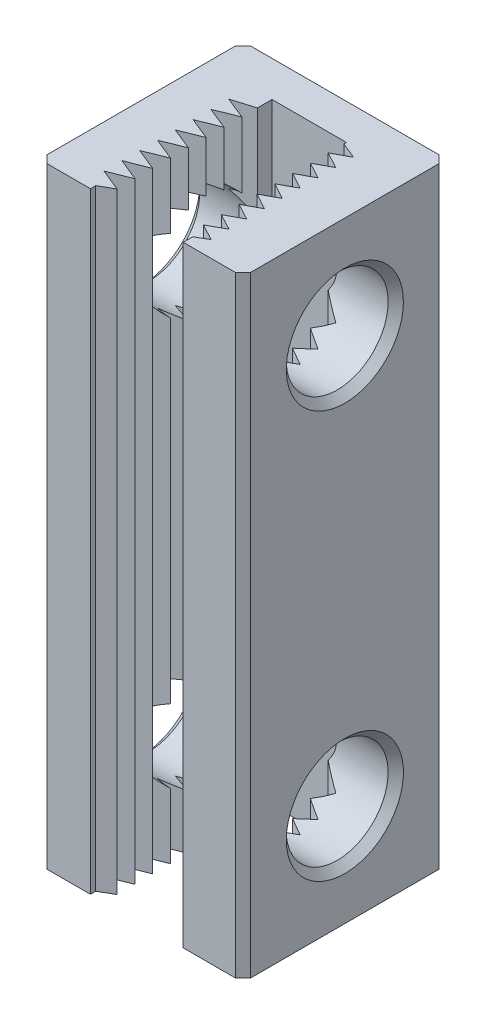
SolidWorks part; units mm, degrees
ref_plane "Front Plane" through (0, 0, 0) normal (0, 0, 1) x (1, 0, 0)
ref_plane "Top Plane" through (0, 0, 0) normal (0, 1, 0) x (1, 0, 0)
ref_plane "Right Plane" through (0, 0, 0) normal (1, 0, 0) x (0, 0, -1)
sketch "Sketch1" plane through (0, 0, 0) normal (0, 1, 0) x (1, 0, 0)
  line L1 (0, 0) -> (8, 0)
  line L2 (0, 0) -> (0, 8)
  line L3 (0, 8) -> (8, 8)
  line L4 (8, 0) -> (8, 8)
  dimension "D1" = 8
  dimension "D2" = 8
extrude "Boss-Extrude1" add sketch "Sketch1" along normal blind 300
sketch "Sketch2" plane through (0, 0, 0) normal (0, -1, 0) x (1, 0, 0)
  line L0 (5.652, 0) -> (2.0084, 0)
  line L1 (2.0084, 0) -> (2.0084, -0.2082)
  line L2 (2.0084, -0.2082) -> (2.54, -0.5151)
  line L3 (2.54, -0.5151) -> (1.6737, -0.8651)
  line L4 (1.6737, -0.8651) -> (2.54, -1.2151)
  line L5 (2.54, -1.2151) -> (1.6737, -1.5727)
  line L6 (1.6737, -1.5727) -> (2.54, -1.9151)
  line L7 (2.54, -1.9151) -> (1.6737, -2.2651)
  line L8 (1.6737, -2.2651) -> (2.54, -2.6151)
  line L9 (2.54, -2.6151) -> (1.6737, -2.9651)
  line L10 (1.6737, -2.9651) -> (2.54, -3.3151)
  line L11 (2.54, -3.3151) -> (1.6737, -3.6651)
  line L12 (1.6737, -3.6651) -> (2.54, -4.0151)
  line L13 (2.54, -4.0151) -> (1.6737, -4.3651)
  line L14 (1.6737, -4.3651) -> (2.54, -4.7151)
  line L15 (2.54, -4.7151) -> (1.6737, -5.0651)
  line L16 (1.6737, -5.0651) -> (2.54, -5.4151)
  line L17 (2.54, -5.4151) -> (1.6737, -5.7651)
  line L18 (1.6737, -5.7651) -> (2.54, -6.0264)
  line L19 (2.54, -6.0264) -> (2.54, -6.6)
  line L20 (2.54, -6.6) -> (5.46, -6.6)
  line L21 (5.46, -6.6) -> (5.46, -6.4988)
  line L22 (5.46, -6.4988) -> (6.1067, -6.2375)
  line L23 (6.1067, -6.2375) -> (5.46, -5.8875)
  line L24 (5.46, -5.8875) -> (6.1067, -5.5375)
  line L25 (6.1067, -5.5375) -> (5.46, -5.1875)
  line L26 (5.46, -5.1875) -> (6.1067, -4.8375)
  line L27 (6.1067, -4.8375) -> (5.46, -4.4875)
  line L28 (5.46, -4.4875) -> (6.1067, -4.1375)
  line L29 (6.1067, -4.1375) -> (5.46, -3.7875)
  line L30 (5.46, -3.7875) -> (6.1067, -3.4375)
  line L31 (6.1067, -3.4375) -> (5.46, -3.0875)
  line L32 (5.46, -3.0875) -> (6.1067, -2.7375)
  line L33 (6.1067, -2.7375) -> (5.46, -2.3875)
  line L34 (5.46, -2.3875) -> (6.1067, -2.0375)
  line L35 (6.1067, -2.0375) -> (5.46, -1.6875)
  line L36 (5.46, -1.6875) -> (6.1067, -1.3451)
  line L37 (6.1067, -1.3451) -> (5.46, -0.9875)
  line L38 (5.46, -0.9875) -> (6.1067, -0.6375)
  line L39 (6.1067, -0.6375) -> (5.652, -0.375)
  line L40 (5.652, -0.375) -> (5.652, 0)
  line L41 (0, -8) -> (0, 0) construction
  line L42 (8, -8) -> (0, -8) construction
  line L43 (0, 0) -> (8, 0) construction
  point P53 (4, -6.6)
  dimension "D1" = 2.92
  dimension "D2" = 0.8663
  dimension "D3" = 6.6
  dimension "D4" = 0.6467
  dimension "D5" = 4.433
  dimension "D6" = 4
extrude "Cut-Extrude1" cut sketch "Sketch2" against normal through all contours L0 L1 L2 L3 L4 L5 L6 L7 L8 L9 L10 L11 L12 L13 L14 L15 L16 L17 L18 L19 L20 L21 L22 L23 L24 L25 L26 L27 L28 L29 L30 L31 L32 L33 L34 L35 L36 L37 L38 L39 L40
sketch "Sketch3" plane through (8, 0, 0) normal (1, 0, 0) x (0, 0, -1)
  line L0 (0, 0) -> (8, 0) construction
  line L1 (8, 300) -> (8, 0) construction
  circle A0 centre (4, 4) radius 2
  dimension "D1" = 4
  dimension "D2" = 4
  dimension "D3" = 4
extrude "Cut-Extrude2" cut sketch "Sketch3" against normal through all
chamfer "Chamfer1" distance 0.3 angle 45 2 edges at (0, 4, -6) (8, 4, -6)
chamfer "Chamfer2" distance 0.3 angle 45 4 edges at (0, 150, -8) (0, 150, 0) (8, 150, -8) (8, 150, 0)
pattern_linear "LPattern1" count 19 spacing 16 along (0, 1, 0) of "Cut-Extrude2", "Chamfer1"
sketch "Sketch4" plane through (8, 0, 0) normal (1, 0, 0) x (0, 0, -1)
  line L0 (0.3, 300) -> (7.7, 300) construction
  line L1 (8, 300) -> (0, 300)
  line L2 (8, 300) -> (8, 24)
  line L3 (8, 24) -> (0, 24)
  line L4 (0, 300) -> (0, 24)
  line L5 (0, 0) -> (0, 300) construction
  line L6 (8, 300) -> (8, 0) construction
  line L7 (0.3, 0) -> (7.7, 0) construction
  dimension "D1" = 24
extrude "Cut-Extrude3" cut sketch "Sketch4" against normal through all
